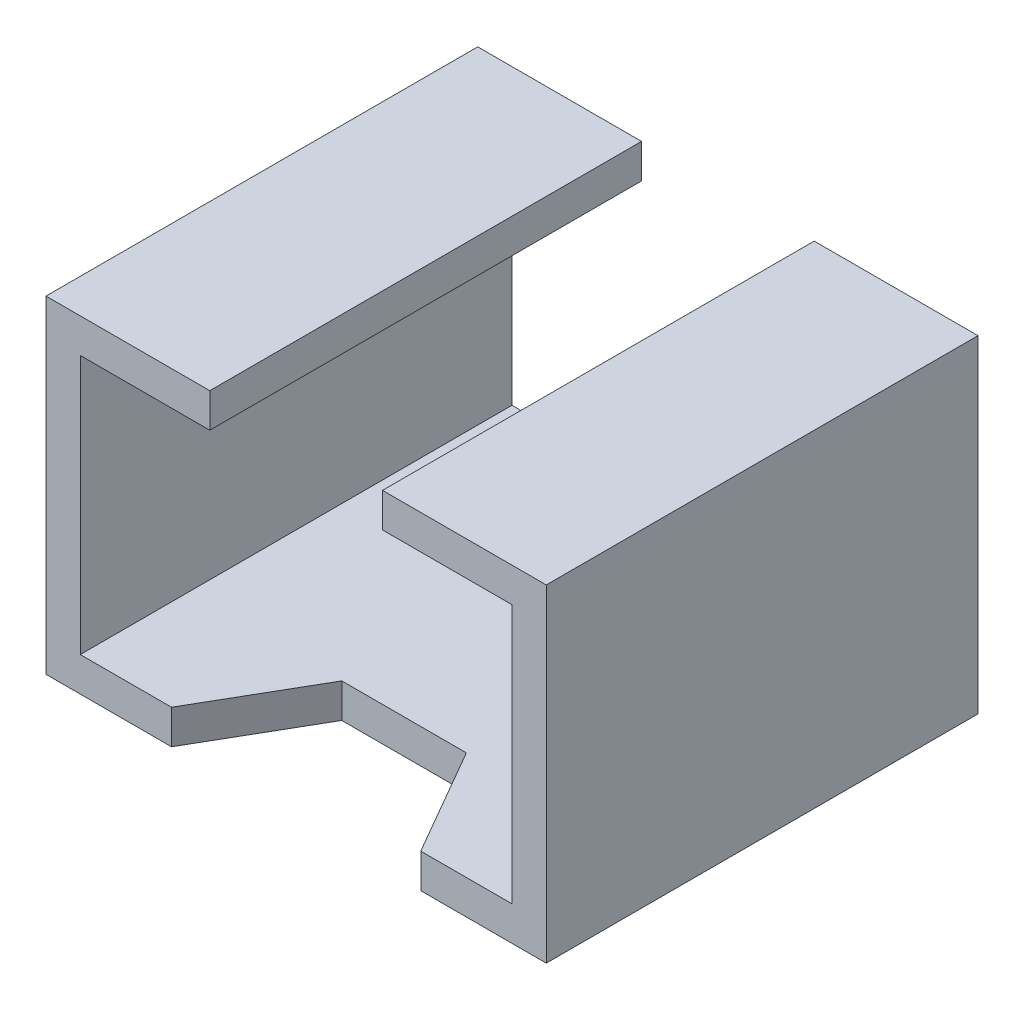
SolidWorks part; units mm, degrees
ref_plane "Alzado" through (0, 0, 0) normal (0, 0, 1) x (1, 0, 0)
ref_plane "Planta" through (0, 0, 0) normal (0, 1, 0) x (1, 0, 0)
ref_plane "Vista lateral" through (0, 0, 0) normal (1, 0, 0) x (0, 0, -1)
sketch "Croquis1" plane through (0, 0, 0) normal (0, 0, 1) x (1, 0, 0)
  line L0 (-50, 0) -> (50, 0)
  line L1 (50, 0) -> (50, 60)
  line L2 (50, 60) -> (20, 60)
  line L3 (-50, 0) -> (-50, 60)
  line L4 (-50, 60) -> (-20, 60)
  line L5 (-57.9375, 67.9375) -> (-20, 67.9375)
  line L6 (-57.9375, -7.9375) -> (-57.9375, 67.9375)
  line L7 (-57.9375, -7.9375) -> (57.9375, -7.9375)
  line L8 (57.9375, -7.9375) -> (57.9375, 67.9375)
  line L9 (57.9375, 67.9375) -> (20, 67.9375)
  line L10 (-20, 60) -> (-20, 67.9375)
  line L11 (20, 60) -> (20, 67.9375)
  dimension "D1" = 100
  dimension "D2" = 60
  dimension "D3" = 30
  dimension "D4" = 7.9375
extrude "Saliente-Extruir1" add sketch "Croquis1" along normal mid plane 100
sketch "Croquis2" plane through (0, -7.9375, 0) normal (0, -1, 0) x (1, 0, 0)
  line L0 (-28.8675, -50) -> (28.8675, -50)
  line L4 (28.8675, -50) -> (14.4338, -25)
  line L5 (14.4338, -25) -> (-14.4338, -25)
  line L6 (-14.4338, -25) -> (-28.8675, -50)
  line L7 (-8.6498, -75) -> (20.2177, -75) [skipped]
  line L8 (23.0966, -59.9955) -> (30.3135, -47.4955) [skipped]
  line L9 (-27.4215, -52.5045) -> (-20.2046, -65.0045) [skipped]
  line L10 (-57.9375, -50) -> (57.9375, -50) construction
  line L11 (0, 8.4893) -> (0, -70.2717) construction
  line L12 (-33.1684, 0) -> (23.2096, 0) construction
  line L13 (-28.8675, 50) -> (28.8675, 50)
  line L14 (28.8675, 50) -> (14.4338, 25)
  line L15 (14.4338, 25) -> (-14.4338, 25)
  line L16 (-14.4338, 25) -> (-28.8675, 50)
  circle A0 centre (0, -50) radius 25 construction
  circle A1 centre (0, 50) radius 25 construction
  point P3 (0, -25)
  point P19 (0, -50)
  dimension "D2" = 50
  dimension "D1" = 25
  dimension "D3" = 28.8675
  dimension "D4" = 28.8675
extrude "Cortar-Extruir1" cut sketch "Croquis2" against normal blind 10
